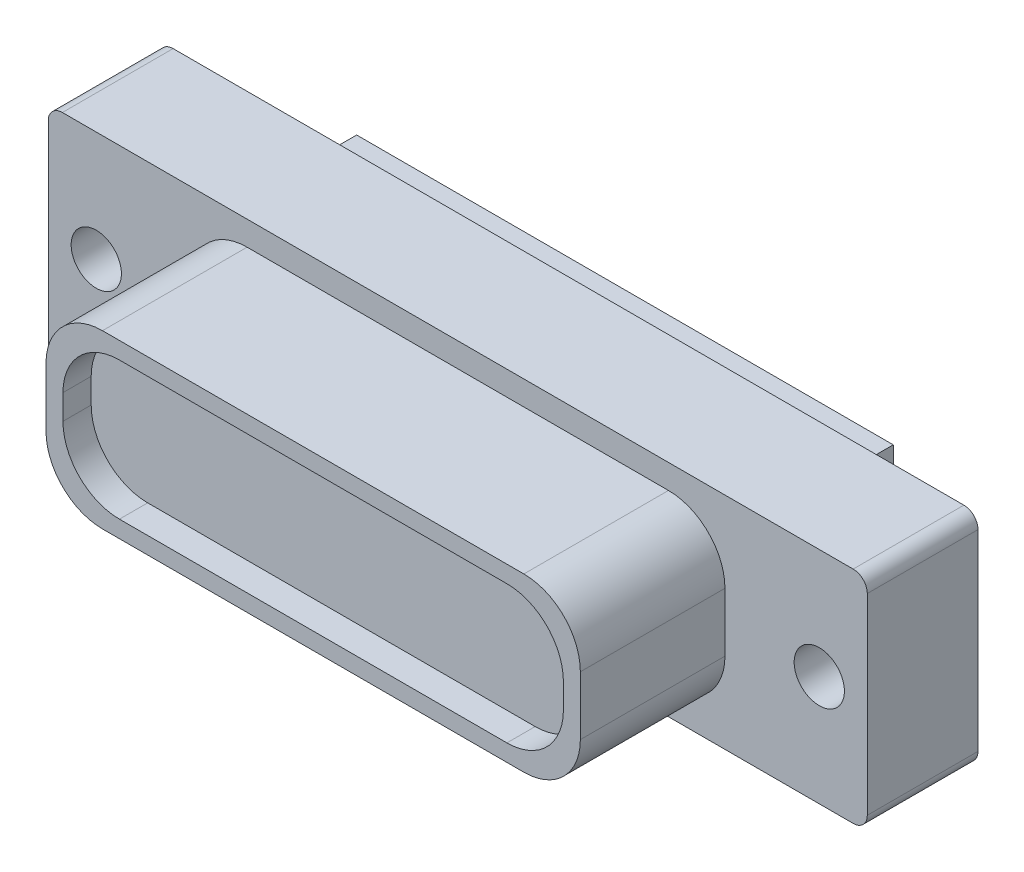
SolidWorks part; units mm, degrees
ref_plane "Front Plane" through (0, 0, 0) normal (0, 0, 1) x (1, 0, 0)
ref_plane "Top Plane" through (0, 0, 0) normal (0, 1, 0) x (1, 0, 0)
ref_plane "Right Plane" through (0, 0, 0) normal (1, 0, 0) x (0, 0, -1)
sketch "Sketch1" plane through (0, 0, 0) normal (0, 0, 1) x (1, 0, 0)
  line L1 (-18.415, -4.953) -> (18.415, -4.953)
  line L2 (-18.415, -4.953) -> (-18.415, 4.953)
  line L3 (-18.415, 4.953) -> (18.415, 4.953)
  line L4 (18.415, -4.953) -> (18.415, 4.953)
  line L5 (-18.415, -4.953) -> (18.415, 4.953) construction
  line L6 (-18.415, 4.953) -> (18.415, -4.953) construction
  point P0 (0, 0)
  dimension "D1" = 36.83
  dimension "D2" = 9.906
extrude "Base" add sketch "Sketch1" along normal blind 4.9784
sketch "Sketch2" plane through (0, 0, 4.9784) normal (0, 0, 1) x (1, 0, 0)
  line L1 (-9.4742, -3.8608) -> (9.4742, -3.8608)
  line L2 (-12.0142, -1.3208) -> (-12.0142, 1.3208)
  line L3 (-9.4742, 3.8608) -> (9.4742, 3.8608)
  line L4 (12.0142, -1.3208) -> (12.0142, 1.3208)
  line L5 (-12.0142, -3.8608) -> (12.0142, 3.8608) construction
  line L6 (-12.0142, 3.8608) -> (12.0142, -3.8608) construction
  arc A0 (12.0142, 1.3208) -> (9.4742, 3.8608) centre (9.4742, 1.3208) ccw
  arc A1 (9.4742, -3.8608) -> (12.0142, -1.3208) centre (9.4742, -1.3208) ccw
  arc A2 (-9.4742, -3.8608) -> (-12.0142, -1.3208) centre (-9.4742, -1.3208) cw
  arc A3 (-9.4742, 3.8608) -> (-12.0142, 1.3208) centre (-9.4742, 1.3208) ccw
  point P0 (0, 0)
  dimension "D3" = 2.54
  dimension "D1" = 7.7216
  dimension "D2" = 24.0284
extrude "Boss-Extrude2" add sketch "Sketch2" along normal blind 6.5024
hole_wizard "#4-40 Tapped Hole1" positions "Sketch4" profile "Sketch3" tap size "#4-40" standard "ANSI Inch"
sketch "Sketch4" plane through (0, 0, 4.9784) normal (0, 0, 1) x (1, 0, 0)
  line L0 (0, 0) -> (0, 8.5745) construction
  point P0 (-16.256, 0)
  point P2 (16.256, 0)
  dimension "D1" = 32.512
sketch "Sketch3" plane through (-16.256, 0, 4.9784) normal (1, 0, 0) x (0, -1, 0)
  line L0 (0, 0) -> (0, 8.2738)
  line L1 (0, 8.2738) -> (1.1303, 7.5946)
  line L2 (1.1303, 7.5946) -> (1.1303, 0)
  line L5 (1.1303, 0) -> (0, 0)
  line L10 (0, 8.2738) -> (-1.1303, 7.5946) construction
  line L11 (0, -6.35) -> (0, 107.95) construction
  dimension "Tap Drill Dia." = 2.2606
  dimension "Tap Drill Depth" = 7.5946
  dimension "Drill Angle" = 118
cosmetic thread "Hole Thread1" parameters "D1"=4.9784, "D2"=2.8448
cosmetic thread "Hole Thread2" parameters "D1"=4.9784, "D2"=2.8448
sketch "Sketch5" plane through (0, 0, 0) normal (0, 0, -1) x (-1, 0, 0)
  line L1 (-12.065, -3.175) -> (12.065, -3.175)
  line L2 (-12.065, -3.175) -> (-12.065, 3.175)
  line L3 (-12.065, 3.175) -> (12.065, 3.175)
  line L4 (12.065, -3.175) -> (12.065, 3.175)
  line L5 (-12.065, -3.175) -> (12.065, 3.175) construction
  line L6 (-12.065, 3.175) -> (12.065, -3.175) construction
  point P0 (0, 0)
  dimension "D1" = 24.13
  dimension "D2" = 6.35
extrude "Boss-Extrude3" add sketch "Sketch5" along normal blind 2.54
sketch "Sketch6" plane through (0, 0, 11.4808) normal (0, 0, 1) x (1, 0, 0)
  line L0 (9.4742, 3.8608) -> (-9.4742, 3.8608) construction
  line L1 (-8.7122, -3.0988) -> (8.7122, -3.0988)
  line L2 (-11.2522, -0.5588) -> (-11.2522, 0.5588)
  line L3 (-8.7122, 3.0988) -> (8.7122, 3.0988)
  line L4 (11.2522, -0.5588) -> (11.2522, 0.5588)
  line L5 (-11.2522, -3.0988) -> (11.2522, 3.0988) construction
  line L6 (-11.2522, 3.0988) -> (11.2522, -3.0988) construction
  line L7 (12.0142, -1.3208) -> (12.0142, 1.3208) construction
  arc A0 (-8.7122, -3.0988) -> (-11.2522, -0.5588) centre (-8.7122, -0.5588) cw
  arc A1 (8.7122, -3.0988) -> (11.2522, -0.5588) centre (8.7122, -0.5588) ccw
  arc A2 (11.2522, 0.5588) -> (8.7122, 3.0988) centre (8.7122, 0.5588) ccw
  arc A3 (-8.7122, 3.0988) -> (-11.2522, 0.5588) centre (-8.7122, 0.5588) ccw
  point P0 (0, 0)
  dimension "D3" = 2.54
  dimension "D1" = 0.762
  dimension "D2" = 0.762
extrude "Cut-Extrude1" cut sketch "Sketch6" against normal blind 1.27
fillet "Fillet1" radius 0.635 4 edges at (-18.415, -4.953, 2.4892) (18.415, -4.953, 2.4892) (18.415, 4.953, 2.4892) (-18.415, 4.953, 2.4892)
